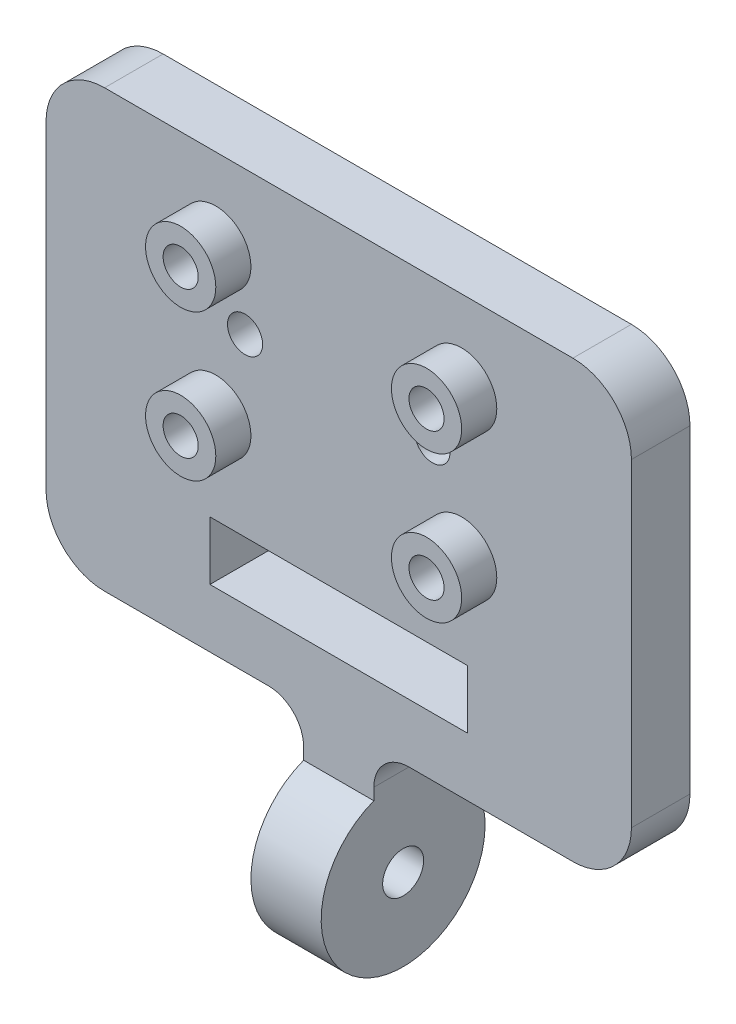
SolidWorks part; units mm, degrees
ref_plane "Front" through (0, 0, 0) normal (0, 0, 1) x (1, 0, 0)
ref_plane "Top" through (0, 0, 0) normal (0, 1, 0) x (1, 0, 0)
ref_plane "Right" through (0, 0, 0) normal (1, 0, 0) x (0, 0, -1)
sketch "Esquisse1" plane through (0, 0, 0) normal (0, 0, 1) x (1, 0, 0)
  line L1 (-11.123, 11.7647) -> (38.877, 11.7647)
  line L2 (-11.123, 11.7647) -> (-11.123, -36.2353)
  line L3 (-11.123, -36.2353) -> (38.877, -36.2353)
  line L4 (38.877, 11.7647) -> (38.877, -36.2353)
  dimension "D1" = 50
  dimension "D2" = 48
extrude "Boss.-Extru.1" add sketch "Esquisse1" along normal blind 5
sketch "Esquisse2" plane through (0, 0, 5) normal (0, 0, 1) x (1, 0, 0)
  line L0 (-11.123, 11.7647) -> (-11.123, -36.2353) construction
  line L1 (38.877, 11.7647) -> (-11.123, 11.7647) construction
  circle A0 centre (3.377, -5.9853) radius 3
  circle A1 centre (3.377, -5.9853) radius 1.5
  dimension "D1" = 14.5
  dimension "D2" = 17.75
extrude "Boss.-Extru.2" add sketch "Esquisse2" along normal blind 3
pattern_linear "Répétition linéaire1" count 2 spacing 21 along (1, 0, 0) count 2 spacing 12.5 along (0, -1, 0) of "Boss.-Extru.2"
ref_plane "Plan1" through (0, -36.2353, 0) normal (0, -1, 0) x (-1, 0, 0)
sketch "Esquisse4" plane through (0, -36.2353, 0) normal (0, -1, 0) x (-1, 0, 0)
  line L0 (11.123, 0) -> (-38.877, 0) construction
  line L1 (-16.877, 0) -> (-10.877, 0)
  line L2 (-16.877, 0) -> (-16.877, -5)
  line L3 (-16.877, -5) -> (-10.877, -5)
  line L4 (-10.877, 0) -> (-10.877, -5)
  line L5 (11.123, -5) -> (-38.877, -5) construction
  line L6 (-38.877, -5) -> (-38.877, 0) construction
  dimension "D1" = 6
  dimension "D2" = 22
extrude "Boss.-Extru.3" add sketch "Esquisse4" along normal blind 4
ref_plane "Plan2" through (10.877, 0, 0) normal (-1, 0, 0) x (0, 0, 1)
sketch "Esquisse5" plane through (10.877, 0, 0) normal (-1, 0, 0) x (0, 0, 1)
  circle A0 centre (2.5, -46.7736) radius 7
extrude "Boss.-Extru.4" add sketch "Esquisse5" against normal blind 6
sketch "Esquisse6" plane through (10.877, 0, 0) normal (-1, 0, 0) x (0, 0, 1)
  circle A2 centre (2.5, -46.7736) radius 7
  circle A3 centre (2.5, -46.7736) radius 1.75
extrude "Enlèv. mat.-Extru.1" cut sketch "Esquisse6" against normal blind 6 contours A3
sketch "Esquisse7" plane through (0, 0, 5) normal (0, 0, 1) x (1, 0, 0)
  line L0 (-11.123, 11.7647) -> (-11.123, -36.2353) construction
  line L1 (38.877, 11.7647) -> (-11.123, 11.7647)
  line L2 (38.877, 11.7647) -> (38.877, 1.0066)
  line L3 (38.877, 1.0066) -> (-11.123, 1.0066)
  line L4 (-11.123, 11.7647) -> (-11.123, 1.0066)
extrude "Enlèv. mat.-Extru.2" cut sketch "Esquisse7" against normal blind 10
fillet "Congé2" radius 5 4 edges at (38.877, -36.2353, 2.5) (38.877, 1.0066, 2.5) (-11.123, 1.0066, 2.5) (-11.123, -36.2353, 2.5)
fillet "Congé3" radius 3 2 edges at (10.877, -36.2353, 2.5) (16.877, -36.2353, 2.5)
ref_plane "Plan3" through (0, 0, 15) normal (0, 0, 1) x (1, 0, 0)
sketch "Esquisse9" plane through (0, 0, 15) normal (0, 0, 1) x (1, 0, 0)
  circle A0 centre (3.377, -5.9853) radius 1.5
  circle A1 centre (24.377, -5.9853) radius 1.5
  circle A2 centre (24.377, -18.4853) radius 1.5
  circle A3 centre (3.377, -18.4853) radius 1.5
extrude "Enlèv. mat.-Extru.3" cut sketch "Esquisse9" against normal through all
sketch "Esquisse10" plane through (0, 0, 5) normal (0, 0, 1) x (1, 0, 0)
  line L0 (-11.123, -28.7353) -> (2.877, -28.7353) construction
  line L1 (2.877, -26.2353) -> (24.877, -26.2353)
  line L2 (2.877, -26.2353) -> (2.877, -31.2353)
  line L3 (2.877, -31.2353) -> (24.877, -31.2353)
  line L4 (24.877, -26.2353) -> (24.877, -31.2353)
  line L5 (-11.123, -3.9934) -> (-11.123, -31.2353) construction
  line L6 (24.877, -28.7353) -> (38.877, -28.7353) construction
  line L7 (38.877, -31.2353) -> (38.877, -3.9934) construction
  line L8 (-6.123, -36.2353) -> (7.877, -36.2353) construction
  dimension "D1" = 5
  dimension "D2" = 5
  dimension "D3" = 22
extrude "Enlèv. mat.-Extru.4" cut sketch "Esquisse10" against normal blind 10
sketch "Esquisse11" plane through (0, 0, 0) normal (0, 0, -1) x (-1, 0, 0)
  line L0 (-18.877, -11.2353) -> (-8.877, -11.2353) construction
  line L1 (-21.877, -11.2353) -> (-38.877, -11.2353) construction
  line L2 (-38.877, -31.2353) -> (-38.877, -3.9934) construction
  line L3 (-19.877, -36.2353) -> (-33.877, -36.2353) construction
  line L4 (-5.877, -11.2353) -> (11.123, -11.2353) construction
  line L5 (11.123, -3.9934) -> (11.123, -31.2353) construction
  circle A2 centre (-21.877, -11.2353) radius 3
  circle A3 centre (-5.877, -11.2353) radius 3
  dimension "D2" = 16
  dimension "D1" = 25
extrude "Boss.-Extru.5" add sketch "Esquisse11" along normal blind 3
ref_plane "Plan4" through (0, 0, -3) normal (0, 0, -1) x (-1, 0, 0)
sketch "Esquisse12" plane through (0, 0, -3) normal (0, 0, -1) x (-1, 0, 0)
  circle A0 centre (-21.877, -11.2353) radius 1.5
  circle A1 centre (-5.877, -11.2353) radius 1.5
extrude "Enlèv. mat.-Extru.5" cut sketch "Esquisse12" against normal through all
